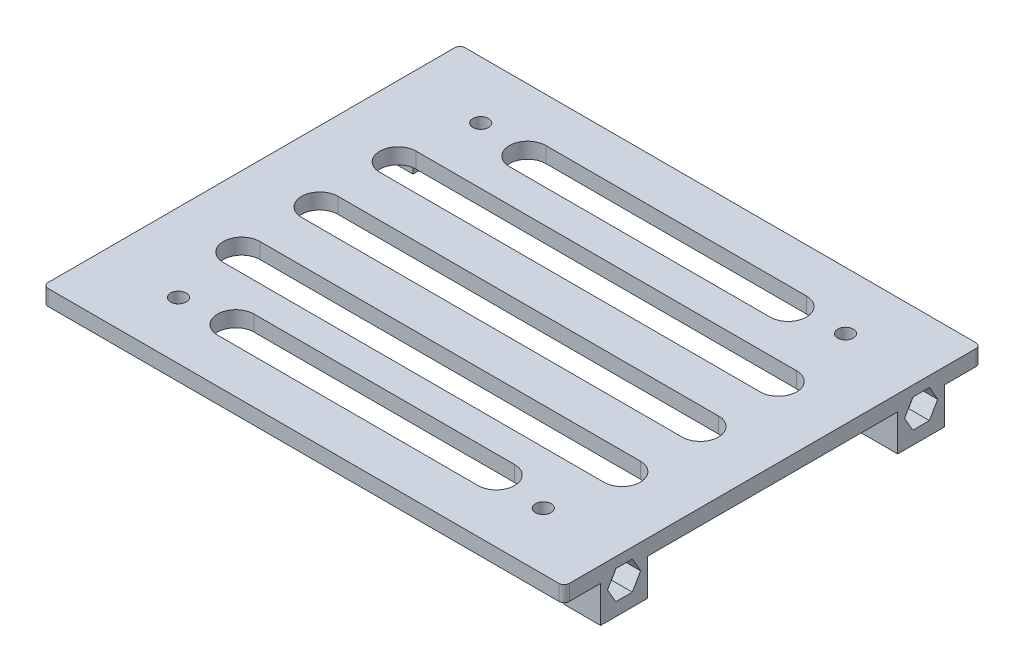
SolidWorks part; units mm, degrees
ref_plane "前视基准面" through (0, 0, 0) normal (0, 0, 1) x (1, 0, 0)
ref_plane "上视基准面" through (0, 0, 0) normal (0, 1, 0) x (1, 0, 0)
ref_plane "右视基准面" through (0, 0, 0) normal (1, 0, 0) x (0, 0, -1)
sketch "草图1" plane through (0, 0, 0) normal (0, 1, 0) x (1, 0, 0)
  line L0 (0, -51.3889) -> (0, 63.5684) construction
  line L1 (-49, 40) -> (49, 40)
  line L2 (-50, 39) -> (-50, -39)
  line L3 (-49, -40) -> (49, -40)
  line L4 (50, 39) -> (50, -39)
  line L5 (-50, 40) -> (50, -40) construction
  line L6 (-50, -40) -> (50, 40) construction
  line L7 (0, 0) -> (0, 29) construction
  line L10 (-85.9228, 29) -> (94.3122, 29) construction
  line L11 (-35, 61.3925) -> (-35, -43.8744) construction
  arc A2 (-50, -39) -> (-49, -40) centre (-49, -39) ccw
  arc A3 (49, -40) -> (50, -39) centre (49, -39) ccw
  arc A4 (49, 40) -> (50, 39) centre (49, 39) cw
  arc A5 (-49, 40) -> (-50, 39) centre (-49, 39) ccw
  point P0 (0, 0)
  dimension "D5" = 1
  dimension "D1" = 100
  dimension "D2" = 80
  dimension "D3" = 29
  dimension "D4" = 35
extrude "凸台-拉伸1" add sketch "草图1" along normal blind 10
sketch "草图2" plane through (0, 0, 0) normal (0, -1, 0) x (-1, 0, 0)
  line L0 (-50, 33) -> (-43, 33)
  line L5 (-50, -39) -> (-50, 39) construction
  line L7 (0, -42.3904) -> (0, 54.3074) construction
  line L8 (43, 24) -> (50, 24)
  line L12 (50, 40) -> (-50, 40)
  line L13 (50, 40) -> (50, 33)
  line L14 (-66.5026, 28.5) -> (89.8167, 28.5) construction
  line L15 (-62.9642, -28.5) -> (91.7122, -28.5) construction
  line L21 (-43, 33) -> (-43, 24)
  line L22 (-43, 24) -> (-50, 24)
  line L23 (50, -40) -> (-50, -40)
  line L24 (-50, 40) -> (-50, 33)
  line L25 (50, 40) -> (-50, -40) construction
  line L26 (50, -40) -> (-50, 40) construction
  line L27 (43, 33) -> (43, 24)
  line L28 (50, 33) -> (43, 33)
  line L29 (-62.9642, 0) -> (91.7122, 0) construction
  line L30 (43, -24) -> (50, -24)
  line L31 (43, -33) -> (43, -24)
  line L32 (50, -33) -> (43, -33)
  line L33 (-43, -24) -> (-50, -24)
  line L34 (-43, -33) -> (-43, -24)
  line L35 (-50, -33) -> (-43, -33)
  line L36 (-50, 24) -> (-50, -24)
  line L37 (50, 24) -> (50, -24)
  line L38 (50, -33) -> (50, -40)
  line L39 (-50, -33) -> (-50, -40)
  point P8 (0, 0)
  dimension "D3" = 57
  dimension "D1" = 4.5
  dimension "D2" = 28.5
  dimension "D4" = 9
  dimension "D5" = 7
extrude "切除-拉伸1" cut sketch "草图2" against normal blind 7
sketch "草图5" plane through (-50, 0, 0) normal (-1, 0, 0) x (0, 0, 1)
  line L0 (-45.9184, 5.2485) -> (59.6696, 5.2485) construction
  line L1 (0, -2.3242) -> (0, 18.2426) construction
  line L2 (30.0877, 7.9985) -> (31.6754, 5.2485)
  line L3 (-25.3246, 5.2485) -> (-26.9123, 7.9985)
  line L4 (-26.9123, 7.9985) -> (-30.0877, 7.9985)
  line L5 (-30.0877, 7.9985) -> (-31.6754, 5.2485)
  line L6 (-31.6754, 5.2485) -> (-30.0877, 2.4985)
  line L7 (-30.0877, 2.4985) -> (-26.9123, 2.4985)
  line L8 (-26.9123, 2.4985) -> (-25.3246, 5.2485)
  line L9 (31.6754, 5.2485) -> (30.0877, 2.4985)
  line L10 (30.0877, 2.4985) -> (26.9123, 2.4985)
  line L11 (26.9123, 2.4985) -> (25.3246, 5.2485)
  line L12 (25.3246, 5.2485) -> (26.9123, 7.9985)
  line L13 (26.9123, 7.9985) -> (30.0877, 7.9985)
  circle A0 centre (-28.5, 5.2485) radius 2.75 construction
  point P6 (-28.5, 2.4985)
  dimension "D1" = 5.5
  dimension "D2" = 28.5
extrude "切除-拉伸3" cut sketch "草图5" against normal blind 4
mirror "镜向1" about plane through (0, 0, 0) normal (1, 0, 0) of "切除-拉伸3"
sketch "草图6" plane through (0, 7, 0) normal (0, -1, 0) x (-1, 0, 0)
  line L0 (0, 45.3807) -> (0, -41.1489) construction
  line L1 (25, -28) -> (-25, -28) construction
  line L2 (25, -31.5) -> (-25, -31.5)
  line L3 (25, -24.5) -> (-25, -24.5)
  line L4 (53.3432, 0) -> (-64.4795, 0) construction
  line L5 (25, 28) -> (-25, 28) construction
  line L6 (25, 31.5) -> (-25, 31.5)
  line L7 (25, 24.5) -> (-25, 24.5)
  line L8 (-36.5, -15.3761) -> (36.5, -15.3761) construction
  line L9 (-36.5, -11.8761) -> (36.5, -11.8761)
  line L10 (-36.5, -18.8761) -> (36.5, -18.8761)
  line L11 (-36.5, -0.3761) -> (36.5, -0.3761) construction
  line L12 (-36.5, 3.1239) -> (36.5, 3.1239)
  line L13 (-36.5, -3.8761) -> (36.5, -3.8761)
  line L14 (-36.5, 14.6239) -> (36.5, 14.6239) construction
  line L15 (-36.5, 18.1239) -> (36.5, 18.1239)
  line L16 (-36.5, 11.1239) -> (36.5, 11.1239)
  arc A0 (25, -31.5) -> (25, -24.5) centre (25, -28) ccw
  arc A1 (-25, -24.5) -> (-25, -31.5) centre (-25, -28) ccw
  arc A2 (25, 31.5) -> (25, 24.5) centre (25, 28) cw
  arc A3 (-25, 24.5) -> (-25, 31.5) centre (-25, 28) cw
  arc A4 (-36.5, -11.8761) -> (-36.5, -18.8761) centre (-36.5, -15.3761) ccw
  arc A5 (36.5, -18.8761) -> (36.5, -11.8761) centre (36.5, -15.3761) ccw
  arc A6 (-36.5, 3.1239) -> (-36.5, -3.8761) centre (-36.5, -0.3761) ccw
  arc A7 (36.5, -3.8761) -> (36.5, 3.1239) centre (36.5, -0.3761) ccw
  arc A8 (-36.5, 18.1239) -> (-36.5, 11.1239) centre (-36.5, 14.6239) ccw
  arc A9 (36.5, 11.1239) -> (36.5, 18.1239) centre (36.5, 14.6239) ccw
  point P5 (0, -28)
  point P14 (0, 28)
  point P21 (0, -15.3761)
  point P30 (0, -0.3761)
  point P37 (0, 14.6239)
  dimension "D1" = 50
  dimension "D2" = 7
  dimension "D3" = 28
  dimension "D4" = 7
  dimension "D5" = 73
  dimension "D6" = 3
extrude "切除-拉伸4" cut sketch "草图6" against normal through all
sketch "草图8" plane through (-46, 0, 0) normal (-1, 0, 0) x (0, 0, 1)
  line L0 (-28.5, 2.4985) -> (-28.5, 7.9985) construction
  line L1 (-30.0877, 2.4985) -> (-26.9123, 2.4985) construction
  line L2 (-26.9123, 7.9985) -> (-30.0877, 7.9985) construction
  line L3 (-31.6754, 5.2485) -> (-25.3246, 5.2485) construction
  circle A0 centre (-28.5, 5.2485) radius 1.5
  dimension "D1" = 3
extrude "切除-拉伸6" cut sketch "草图8" against normal up to next and the other way through all
mirror "镜向2" about plane through (0, 0, 0) normal (1, 0, 0) of "切除-拉伸6" second plane through (0, 0, 0) second plane normal (0, 0, 1)
sketch "草图9" plane through (0, 7, 0) normal (0, -1, 0) x (-1, 0, 0)
  line L0 (58.5327, 0) -> (-69.4909, 0) construction
  line L1 (0, 46.8395) -> (0, -46.5723) construction
  line L2 (61.0718, -29) -> (-76.3064, -29) construction
  line L3 (35, -48.3095) -> (35, 46.8395) construction
  circle A0 centre (35, -29) radius 1.5
  dimension "D3" = 3
  dimension "D1" = 29
  dimension "D2" = 35
extrude "切除-拉伸7" cut sketch "草图9" against normal up to next
mirror "镜向3" about plane through (0, 0, 0) normal (0, 0, 1) of "切除-拉伸7" second plane through (0, 0, 0) second plane normal (1, 0, 0)
